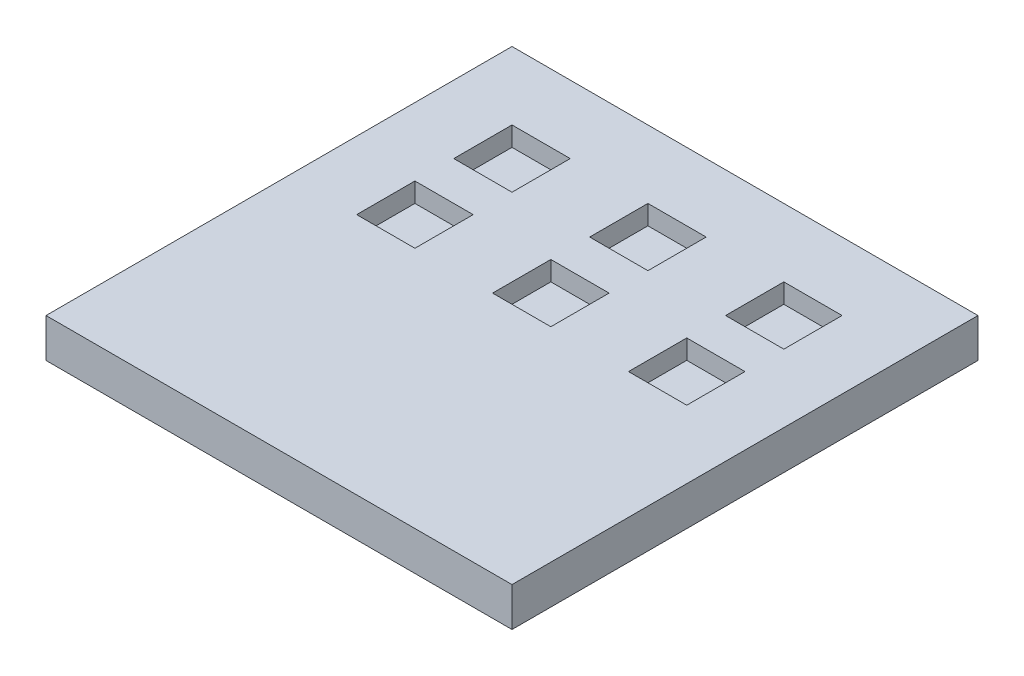
SolidWorks part; units mm, degrees
ref_plane "Front Plane" through (0, 0, 0) normal (0, 0, 1) x (1, 0, 0)
ref_plane "Top Plane" through (0, 0, 0) normal (0, 1, 0) x (1, 0, 0)
ref_plane "Right Plane" through (0, 0, 0) normal (1, 0, 0) x (0, 0, -1)
sketch "Sketch1" plane through (0, 0, 0) normal (0, 1, 0) x (1, 0, 0)
  line L1 (-152.4, -152.4) -> (152.4, -152.4)
  line L2 (-152.4, -152.4) -> (-152.4, 152.4)
  line L3 (-152.4, 152.4) -> (152.4, 152.4)
  line L4 (152.4, -152.4) -> (152.4, 152.4)
  line L5 (-152.4, -152.4) -> (152.4, 152.4) construction
  line L6 (-152.4, 152.4) -> (152.4, -152.4) construction
  point P0 (0, 0)
  dimension "D1" = 304.8
  dimension "D2" = 304.8
extrude "Boss-Extrude1" add sketch "Sketch1" along normal blind 25.4718
sketch "Sketch2" plane through (0, 25.4718, 0) normal (0, 1, 0) x (1, 0, 0)
  line L0 (-152.4, 152.4) -> (-152.4, -152.4) construction
  line L1 (-107.95, 69.85) -> (-69.85, 69.85)
  line L2 (-107.95, 69.85) -> (-107.95, 107.95)
  line L3 (-107.95, 107.95) -> (-69.85, 107.95)
  line L4 (-69.85, 69.85) -> (-69.85, 107.95)
  line L5 (-107.95, 69.85) -> (-69.85, 107.95) construction
  line L6 (-107.95, 107.95) -> (-69.85, 69.85) construction
  line L7 (152.4, 152.4) -> (-152.4, 152.4) construction
  point P0 (-88.9, 88.9)
  dimension "D1" = 38.1
  dimension "D2" = 38.1
  dimension "D3" = 44.45
  dimension "D4" = 44.45
extrude "Cut-Extrude1" cut sketch "Sketch2" against normal blind 12.7
pattern_linear "LPattern1" count 2 spacing 63.5 along (0, 0, 1) count 3 spacing 88.9 along (1, 0, 0) of "Cut-Extrude1"
